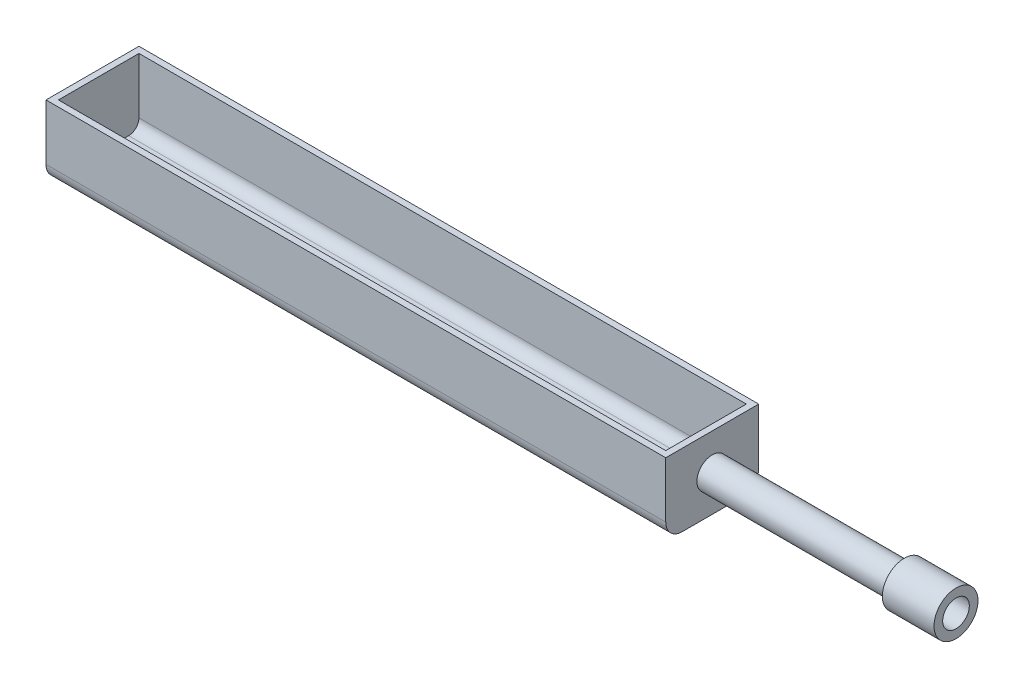
SolidWorks part; units mm, degrees
ref_plane "Front Plane" through (0, 0, 0) normal (0, 0, 1) x (1, 0, 0)
ref_plane "Top Plane" through (0, 0, 0) normal (0, 1, 0) x (1, 0, 0)
ref_plane "Right Plane" through (0, 0, 0) normal (1, 0, 0) x (0, 0, -1)
sketch "Sketch1" plane through (0, 0, 0) normal (1, 0, 0) x (0, 0, -1)
  line L1 (22.5, -17.5) -> (-22.5, -17.5)
  line L2 (22.5, -17.5) -> (22.5, 17.5)
  line L3 (22.5, 17.5) -> (-22.5, 17.5)
  line L4 (-22.5, -17.5) -> (-22.5, 17.5)
  line L5 (22.5, -17.5) -> (-22.5, 17.5) construction
  line L6 (22.5, 17.5) -> (-22.5, -17.5) construction
  point P0 (0, 0)
extrude "Boss-Extrude1" add sketch "Sketch1" along normal blind 300
fillet "Fillet1" radius 8 2 edges at (150, -17.5, -22.5) (150, -17.5, 22.5)
shell "Shell1" thickness 3
ref_plane "Plane1" through (290, 0, 0) normal (1, 0, 0) x (0, 0, -1)
sketch "Sketch3" plane through (290, 0, 0) normal (1, 0, 0) x (0, 0, -1)
  circle A0 centre (0, 0) radius 7.45
  circle A1 centre (0, 0) radius 6.45
  dimension "D1" = 14.9
  dimension "D2" = 1
extrude "Boss-Extrude2" add sketch "Sketch3" along normal blind 103
sketch "Sketch4" plane through (393, 0, 0) normal (1, 0, 0) x (0, 0, -1)
  circle A0 centre (0, 0) radius 10.65
  circle A1 centre (0, 0) radius 6.45
  dimension "D1" = 21.3
extrude "Boss-Extrude3" add sketch "Sketch4" along normal blind 25
